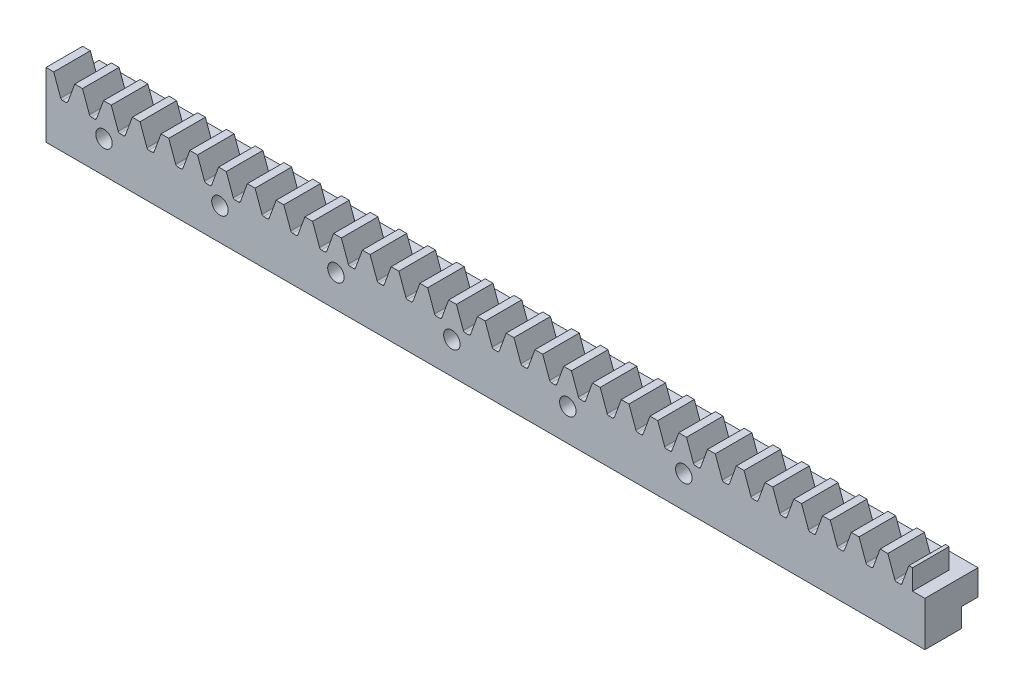
SolidWorks part; units mm, degrees
ref_plane "Front Plane" through (0, 0, 0) normal (0, 0, 1) x (1, 0, 0)
ref_plane "Top Plane" through (0, 0, 0) normal (0, 1, 0) x (1, 0, 0)
ref_plane "Right Plane" through (0, 0, 0) normal (1, 0, 0) x (0, 0, -1)
sketch "Sketch1" plane through (0, 0, 0) normal (0, 0, 1) x (1, 0, 0)
  line L0 (0, 0) -> (-50.8, 0) construction
  line L1 (0, 0) -> (50.8, 0) construction
  line L2 (0, 0) -> (0, 25) construction
  line L3 (-50.8, 22.5) -> (50.8, 22.5) construction
  point P3 (207.264, 0)
  point P7 (0, 25)
sketch "Sketch2" plane through (0, 0, 0) normal (1, 0, 0) x (0, 0, -1)
  line L0 (0, 0) -> (0, 25) construction
  line L1 (5, 25) -> (-5, 25)
  line L2 (0, 12.5) -> (-5, 12.5) construction
  line L3 (0, 12.5) -> (5, 12.5) construction
  line L4 (-5, 25) -> (-5, 0)
  line L5 (-5, 0) -> (5, 0)
  line L6 (5, 0) -> (5, 25)
extrude "Boss-Extrude1" add sketch "Sketch2" along normal mid plane 240
sketch "Sketch3" plane through (0, 0, 0) normal (0, 0, 1) x (1, 0, 0)
  line L0 (-117.8929, 25) -> (-115.8725, 19.4492)
  line L2 (-115.8725, 19.4492) -> (-114.1663, 19.4492)
  line L3 (-114.1663, 19.4492) -> (-112.146, 25)
  line L4 (-117.8929, 25) -> (-112.146, 25)
  line L5 (-117.8929, 25) -> (-120, 25) construction
  line L6 (-112.146, 25) -> (-110.0389, 25) construction
  line L7 (-110.0389, 25) -> (-108.0186, 19.4492) construction
  line L8 (-115.0194, 19.4492) -> (-115.0194, 25) construction
  line L9 (-116.9829, 22.5) -> (-113.0559, 22.5) construction
  line L10 (-113.0559, 22.5) -> (-113.0559, 25) construction
  line L11 (-109.129, 22.5) -> (-109.129, 19.4492) construction
  line L12 (-113.0559, 22.5) -> (-109.129, 22.5) construction
  line L13 (-120, 25) -> (-120, 0) construction
  line L14 (120, 25) -> (-120, 25) construction
  dimension "D1" = 20
  dimension "D2" = 20
  dimension "D3" = 5.5508
  dimension "D4" = 2.5
  dimension "D5" = 7.854
extrude "Cut-Extrude1" cut sketch "Sketch3" against normal through all both and the other way through all
fillet "Fillet1" radius 0.5119 2 edges at (-114.1663, 19.4492, 0) (-115.8725, 19.4492, 0)
pattern_linear "LPattern1" count 30 spacing 7.854 along (1, 0, 0) of "Cut-Extrude1", "Fillet1"
sketch "Esquisse1" plane through (0, 0, 5) normal (0, 0, 1) x (1, 0, 0)
  line L0 (-120, 7.3) -> (120, 7.3)
  line L1 (-120, 25) -> (-120, 0) construction
  line L2 (120, 25) -> (120, 0) construction
  line L3 (120, 7.3) -> (120, 0)
  line L4 (120, 0) -> (-120, 0)
  line L5 (-120, 0) -> (-120, 7.3)
  line L6 (-117.8929, 25) -> (-120, 25) construction
  dimension "D1" = 17.7
extrude "Enlèv. mat.-Extru.1" cut sketch "Esquisse1" against normal through all
sketch "Esquisse6" plane through (0, 0, -5) normal (0, 0, -1) x (-1, 0, 0)
  line L0 (-120, 12.5) -> (120, 12.5)
  line L1 (-120, 7.3) -> (-120, 25) construction
  line L2 (120, 7.3) -> (120, 25) construction
  line L3 (120, 12.5) -> (120, 21.2314)
  line L4 (120, 21.2314) -> (-120, 21.2314)
  line L5 (-120, 21.2314) -> (-120, 12.5)
  line L6 (-120, 7.3) -> (120, 7.3) construction
  dimension "D1" = 5.2
  dimension "D2" = 8.7314
extrude "Boss.-Extru.1" add sketch "Esquisse6" along normal blind 4.5
hole_wizard "Diamètre du perçage Ø4.5 (4.5)1" positions "Esquisse3" profile "Esquisse5" hole size "Ø4.5" standard "Ansi Metric" end condition through all
sketch "Esquisse3" plane through (0, 0, 5) normal (0, 0, 1) x (1, 0, 0)
  line L0 (70, 12.5) -> (70, 19.612) construction
  line L18 (70, 16.056) -> (38.3333, 16.056) construction
  line L19 (38.3333, 16.056) -> (6.6667, 16.056) construction
  line L20 (6.6667, 16.056) -> (-25, 16.056) construction
  line L21 (-25, 16.056) -> (-56.6667, 16.056) construction
  line L22 (-56.6667, 16.056) -> (-88.3333, 16.056) construction
  line L23 (-88.3333, 16.056) -> (-120, 16.056) construction
  line L25 (120, 7.3) -> (-120, 7.3) construction
  line L26 (-120, 25) -> (-120, 7.3) construction
  point P64 (54.1667, 16.056)
  point P66 (22.5, 16.056)
  point P68 (-9.1667, 16.056)
  point P70 (-40.8333, 16.056)
  point P72 (-72.5, 16.056)
  point P74 (-104.1667, 16.056)
  dimension "D1" = 7.112
  dimension "D2" = 5.2
  dimension "D3" = 190
sketch "Esquisse5" plane through (-104.1667, 16.056, 5) normal (1, 0, 0) x (0, -1, 0)
  line L0 (0, 0) -> (0, 14.5)
  line L1 (0, 14.5) -> (2.25, 14.5)
  line L2 (2.25, 14.5) -> (2.25, 0)
  line L5 (2.25, 0) -> (0, 0)
  line L11 (0, -6.35) -> (0, 107.95) construction
  dimension "Diamètre du perçage jusqu'au prochain" = 4.5
  dimension "Profondeur du perçage jusqu'au prochain" = 14.5
sketch "Esquisse8" plane through (0, 0, -9.5) normal (0, 0, -1) x (-1, 0, 0)
  line L0 (120, 19.4492) -> (-120, 19.4492)
  line L1 (120, 25) -> (120, 7.3) construction
  line L2 (-120, 25) -> (-120, 7.3) construction
  line L3 (-120, 19.4492) -> (-120, 21.2314)
  line L4 (120, 21.2314) -> (-120, 21.2314)
  line L5 (-72.9814, 19.4492) -> (-73.9708, 19.4492) construction
  line L6 (120, 21.2314) -> (120, 19.4492)
extrude "Enlèv. mat.-Extru.3" cut sketch "Esquisse8" against normal up to surface (4.5 mm away) up to face at (0, 9.9, -5)
sketch "Esquisse9" plane through (0, 0, -5) normal (0, 0, -1) x (-1, 0, 0)
  line L11 (-115.6194, 25) -> (-116.6194, 25) construction
  line L14 (-120, 25) -> (-115.6194, 25) construction
  line L18 (-116.6194, 25) -> (-116.6194, 19.4492)
  line L19 (-120, 19.4492) -> (120, 19.4492) construction
  line L20 (-116.6194, 19.4492) -> (-120, 19.4492)
  line L21 (-120, 19.4492) -> (-120, 25)
  line L30 (-120, 25) -> (-116.6194, 25)
  dimension "D1" = 1
extrude "Enlèv. mat.-Extru.4" cut sketch "Esquisse9" against normal through all
equation "\"D3@Sketch3\"=(2.2/\"DiamPitch\")+.002"
equation "\"D4@Sketch3\"=1/\"DiamPitch\""
equation "\"D5@Sketch3\"=pi/\"DiamPitch\""
equation "\"D3@LPattern1\"=pi/\"DiamPitch\""
equation "\"D1@LPattern1\"= \"Overall Length@Sketch1\" * 11"
equation "\"E\"= 10mm"
equation "\"Width@Sketch2\"=\"E\""
equation "\"L\"= 240mm"
equation "\"D1@Boss-Extrude1\"=\"L\""
equation "\"PresureAngle\"= 20deg"
equation "\"D2@Sketch3\"=\"PresureAngle\""
equation "\"D1@Sketch3\"=\"PresureAngle\""
equation "\"PitchHT\"= 22.5mm"
equation "\"Hauteur\"= 25mm"
equation "\"DiamPitch\"= 258.064mm"
